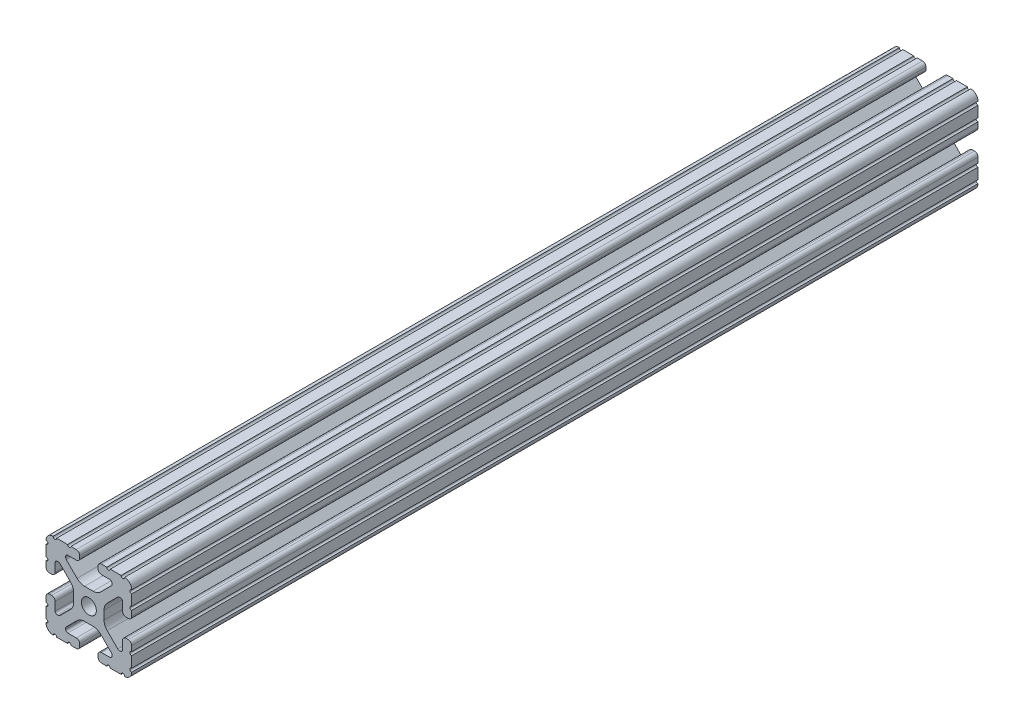
SolidWorks part; units mm, degrees
material "6061 Alloy"
ref_plane "Front Plane" through (0, 0, 0) normal (0, 0, 1) x (1, 0, 0)
ref_plane "Top Plane" through (0, 0, 0) normal (0, 1, 0) x (1, 0, 0)
ref_plane "Right Plane" through (0, 0, 0) normal (1, 0, 0) x (0, 0, -1)
sketch "Sketch1" plane through (0, 0, 0) normal (0, 0, 1) x (1, 0, 0)
  line L0 (0, 25.6181) -> (0, -24.623) construction
  line L1 (-20.8943, 0) -> (20.4607, 0) construction
  line L2 (-10.0229, 12.9148) -> (-5.2522, 8.144)
  line L3 (-10.287, 14.0843) -> (-10.287, 13.5524)
  line L4 (-5.6176, 14.986) -> (-9.3853, 14.986)
  line L5 (-4.064, 17.4964) -> (-4.064, 16.5396)
  line L6 (-7.9742, 19.05) -> (-5.6176, 19.05)
  line L7 (-14.3277, 19.05) -> (-9.4982, 19.05)
  line L8 (-19.05, 9.4961) -> (-19.05, 14.3277)
  line L9 (-19.05, 5.6176) -> (-19.05, 7.9763)
  line L10 (-16.5396, 4.064) -> (-17.4964, 4.064)
  line L11 (-14.986, 9.3853) -> (-14.986, 5.6176)
  line L12 (-13.516, 10.287) -> (-14.0843, 10.287)
  line L13 (-8.1476, 5.2921) -> (-12.8784, 10.0229)
  line L14 (-6.7564, -1.9335) -> (-6.7564, 1.9335)
  line L15 (-12.8784, -10.0229) -> (-8.1476, -5.2921)
  line L16 (-14.0843, -10.287) -> (-13.516, -10.287)
  line L17 (-14.986, -5.6176) -> (-14.986, -9.3853)
  line L18 (-17.4964, -4.064) -> (-16.5396, -4.064)
  line L19 (-19.05, -7.9763) -> (-19.05, -5.6176)
  line L20 (-19.05, -14.3277) -> (-19.05, -9.4961)
  line L21 (-9.4961, -19.05) -> (-14.3277, -19.05)
  line L22 (-5.6176, -19.05) -> (-7.9763, -19.05)
  line L23 (-4.064, -17.4964) -> (-4.064, -16.5396)
  line L24 (10.0229, -12.9148) -> (5.2522, -8.144)
  line L25 (10.287, -14.0843) -> (10.287, -13.5524)
  line L26 (5.6176, -14.986) -> (9.3853, -14.986)
  line L28 (-1.9022, 6.7564) -> (1.9022, 6.7564)
  line L29 (-1.9022, -6.7564) -> (1.9022, -6.7564)
  line L31 (-5.6176, -14.986) -> (-9.3853, -14.986)
  line L32 (-10.287, -14.0843) -> (-10.287, -13.5524)
  line L33 (-10.0229, -12.9148) -> (-5.2522, -8.144)
  line L66 (4.064, -16.5396) -> (4.064, -17.4964)
  line L67 (5.6176, -19.05) -> (7.9763, -19.05)
  line L68 (9.4961, -19.05) -> (14.3277, -19.05)
  line L69 (19.05, -14.3277) -> (19.05, -9.4961)
  line L70 (19.05, -7.9763) -> (19.05, -5.6176)
  line L71 (17.4964, -4.064) -> (16.5396, -4.064)
  line L72 (14.986, -5.6176) -> (14.986, -9.3853)
  line L73 (14.0843, -10.287) -> (13.516, -10.287)
  line L74 (12.8784, -10.0229) -> (8.1476, -5.2921)
  line L75 (6.7564, -1.9335) -> (6.7564, 1.9335)
  line L76 (8.1476, 5.2921) -> (12.8784, 10.0229)
  line L77 (13.516, 10.287) -> (14.0843, 10.287)
  line L78 (14.986, 9.3853) -> (14.986, 5.6176)
  line L79 (16.5396, 4.064) -> (17.4964, 4.064)
  line L80 (19.05, 5.6176) -> (19.05, 7.9763)
  line L81 (19.05, 9.4961) -> (19.05, 14.3277)
  line L82 (14.3277, 19.05) -> (9.4982, 19.05)
  line L83 (7.9742, 19.05) -> (5.6176, 19.05)
  line L84 (4.064, 17.4964) -> (4.064, 16.5396)
  line L85 (5.6176, 14.986) -> (9.3853, 14.986)
  line L86 (10.287, 14.0843) -> (10.287, 13.5524)
  line L87 (10.0229, 12.9148) -> (5.2522, 8.144)
  arc A0 (-10.0229, 12.9148) -> (-10.287, 13.5524) centre (-9.3853, 13.5524) cw
  circle A1 centre (0, 0) radius 3.3274
  arc A2 (-10.287, 14.0843) -> (-9.3853, 14.986) centre (-9.3853, 14.0843) cw
  arc A3 (-4.064, 16.5396) -> (-5.6176, 14.986) centre (-5.6176, 16.5396) cw
  arc A4 (-5.6176, 19.05) -> (-4.064, 17.4964) centre (-5.6176, 17.4964) cw
  arc A5 (-7.9742, 19.05) -> (-9.4982, 19.05) centre (-8.7362, 19.05) cw
  arc A6 (-14.3277, 19.05) -> (-15.8475, 19.05) centre (-15.0876, 18.9933) cw
  arc A7 (-19.05, 15.8475) -> (-15.8475, 19.05) centre (-15.8751, 15.8751) cw
  arc A8 (-19.05, 15.8475) -> (-19.05, 14.3277) centre (-18.9933, 15.0876) cw
  arc A9 (-19.05, 9.4961) -> (-19.05, 7.9763) centre (-18.9933, 8.7362) cw
  arc A10 (-17.4964, 4.064) -> (-19.05, 5.6176) centre (-17.4964, 5.6176) cw
  arc A11 (-14.986, 5.6176) -> (-16.5396, 4.064) centre (-16.5396, 5.6176) cw
  arc A12 (-14.986, 9.3853) -> (-14.0843, 10.287) centre (-14.0843, 9.3853) cw
  arc A13 (-13.516, 10.287) -> (-12.8784, 10.0229) centre (-13.516, 9.3853) cw
  arc A14 (-8.1476, 5.2921) -> (-6.7564, 1.9335) centre (-11.5062, 1.9335) cw
  arc A15 (-6.7564, -1.9335) -> (-8.1476, -5.2921) centre (-11.5062, -1.9335) cw
  arc A16 (-12.8784, -10.0229) -> (-13.516, -10.287) centre (-13.516, -9.3853) cw
  arc A17 (-14.0843, -10.287) -> (-14.986, -9.3853) centre (-14.0843, -9.3853) cw
  arc A18 (-16.5396, -4.064) -> (-14.986, -5.6176) centre (-16.5396, -5.6176) cw
  arc A19 (-19.05, -5.6176) -> (-17.4964, -4.064) centre (-17.4964, -5.6176) cw
  arc A20 (-19.05, -7.9763) -> (-19.05, -9.4961) centre (-18.9933, -8.7362) cw
  arc A21 (-19.05, -14.3277) -> (-19.05, -15.8475) centre (-18.9933, -15.0876) cw
  arc A22 (-15.8475, -19.05) -> (-19.05, -15.8475) centre (-15.8751, -15.8751) cw
  arc A23 (-15.8475, -19.05) -> (-14.3277, -19.05) centre (-15.0876, -18.9933) cw
  arc A24 (-9.4961, -19.05) -> (-7.9763, -19.05) centre (-8.7362, -18.9933) cw
  arc A25 (-4.064, -17.4964) -> (-5.6176, -19.05) centre (-5.6176, -17.4964) cw
  arc A26 (-5.2522, -8.144) -> (-1.9022, -6.7564) centre (-1.9022, -11.494) cw
  arc A27 (1.9022, -6.7564) -> (5.2522, -8.144) centre (1.9022, -11.494) cw
  arc A28 (10.0229, -12.9148) -> (10.287, -13.5524) centre (9.3853, -13.5524) cw
  arc A29 (10.287, -14.0843) -> (9.3853, -14.986) centre (9.3853, -14.0843) cw
  arc A30 (4.064, -16.5396) -> (5.6176, -14.986) centre (5.6176, -16.5396) cw
  arc A31 (-4.064, -16.5396) -> (-5.6176, -14.986) centre (-5.6176, -16.5396) ccw
  arc A32 (-10.287, -14.0843) -> (-9.3853, -14.986) centre (-9.3853, -14.0843) ccw
  arc A33 (-10.0229, -12.9148) -> (-10.287, -13.5524) centre (-9.3853, -13.5524) ccw
  arc A79 (4.064, -17.4964) -> (5.6176, -19.05) centre (5.6176, -17.4964) ccw
  arc A80 (9.4961, -19.05) -> (7.9763, -19.05) centre (8.7362, -18.9933) ccw
  arc A81 (15.8475, -19.05) -> (14.3277, -19.05) centre (15.0876, -18.9933) ccw
  arc A82 (15.8475, -19.05) -> (19.05, -15.8475) centre (15.8751, -15.8751) ccw
  arc A83 (19.05, -14.3277) -> (19.05, -15.8475) centre (18.9933, -15.0876) ccw
  arc A84 (19.05, -7.9763) -> (19.05, -9.4961) centre (18.9933, -8.7362) ccw
  arc A85 (19.05, -5.6176) -> (17.4964, -4.064) centre (17.4964, -5.6176) ccw
  arc A86 (16.5396, -4.064) -> (14.986, -5.6176) centre (16.5396, -5.6176) ccw
  arc A87 (14.0843, -10.287) -> (14.986, -9.3853) centre (14.0843, -9.3853) ccw
  arc A88 (12.8784, -10.0229) -> (13.516, -10.287) centre (13.516, -9.3853) ccw
  arc A89 (6.7564, -1.9335) -> (8.1476, -5.2921) centre (11.5062, -1.9335) ccw
  arc A90 (8.1476, 5.2921) -> (6.7564, 1.9335) centre (11.5062, 1.9335) ccw
  arc A91 (13.516, 10.287) -> (12.8784, 10.0229) centre (13.516, 9.3853) ccw
  arc A92 (14.986, 9.3853) -> (14.0843, 10.287) centre (14.0843, 9.3853) ccw
  arc A93 (14.986, 5.6176) -> (16.5396, 4.064) centre (16.5396, 5.6176) ccw
  arc A94 (17.4964, 4.064) -> (19.05, 5.6176) centre (17.4964, 5.6176) ccw
  arc A95 (19.05, 9.4961) -> (19.05, 7.9763) centre (18.9933, 8.7362) ccw
  arc A96 (19.05, 15.8475) -> (19.05, 14.3277) centre (18.9933, 15.0876) ccw
  arc A97 (19.05, 15.8475) -> (15.8475, 19.05) centre (15.8751, 15.8751) ccw
  arc A98 (14.3277, 19.05) -> (15.8475, 19.05) centre (15.0876, 18.9933) ccw
  arc A99 (7.9742, 19.05) -> (9.4982, 19.05) centre (8.7362, 19.05) ccw
  arc A100 (5.6176, 19.05) -> (4.064, 17.4964) centre (5.6176, 17.4964) ccw
  arc A101 (4.064, 16.5396) -> (5.6176, 14.986) centre (5.6176, 16.5396) ccw
  arc A102 (10.287, 14.0843) -> (9.3853, 14.986) centre (9.3853, 14.0843) ccw
  arc A103 (10.0229, 12.9148) -> (10.287, 13.5524) centre (9.3853, 13.5524) ccw
  arc A104 (1.9022, 6.7564) -> (5.2522, 8.144) centre (1.9022, 11.494) ccw
  arc A105 (-5.2522, 8.144) -> (-1.9022, 6.7564) centre (-1.9022, 11.494) ccw
  dimension "D1" = 6.6548
  dimension "D2" = 19.05
  dimension "D3" = 38.1
  dimension "D4" = 20.574
  dimension "D5" = 13.5128
  dimension "D6" = 4.064
  dimension "D7" = 8.128
  dimension "D8" = 4.064
  dimension "D9" = 12.2936
extrude "Extrude1" add sketch "Sketch1" against normal blind 376.2
